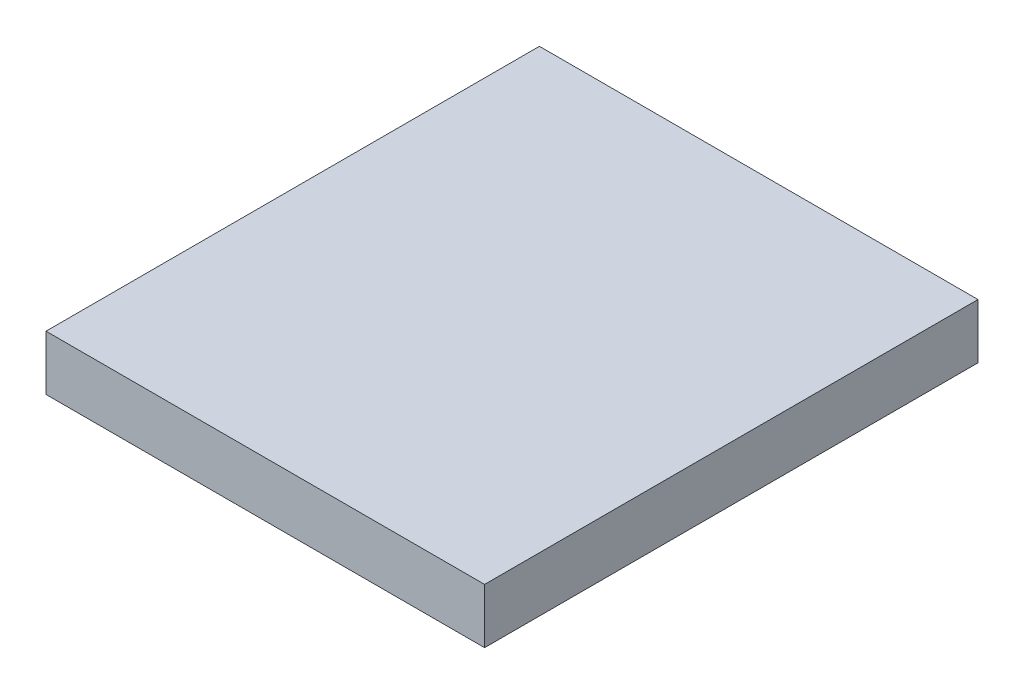
SolidWorks part; units mm, degrees
ref_plane "Front Plane" through (0, 0, 0) normal (0, 0, 1) x (1, 0, 0)
ref_plane "Top Plane" through (0, 0, 0) normal (0, 1, 0) x (1, 0, 0)
ref_plane "Right Plane" through (0, 0, 0) normal (1, 0, 0) x (0, 0, -1)
sketch "Эскиз1" plane through (0, 0, 0) normal (0, 1, 0) x (1, 0, 0)
  line L1 (-8, 9) -> (8, 9)
  line L2 (-8, 9) -> (-8, -9)
  line L3 (-8, -9) -> (8, -9)
  line L4 (8, 9) -> (8, -9)
  line L5 (-8, 9) -> (8, -9) construction
  line L6 (-8, -9) -> (8, 9) construction
  point P0 (0, 0)
  dimension "D1" = 16
  dimension "D2" = 18
extrude "Бобышка-Вытянуть1" add sketch "Эскиз1" along normal blind 2
